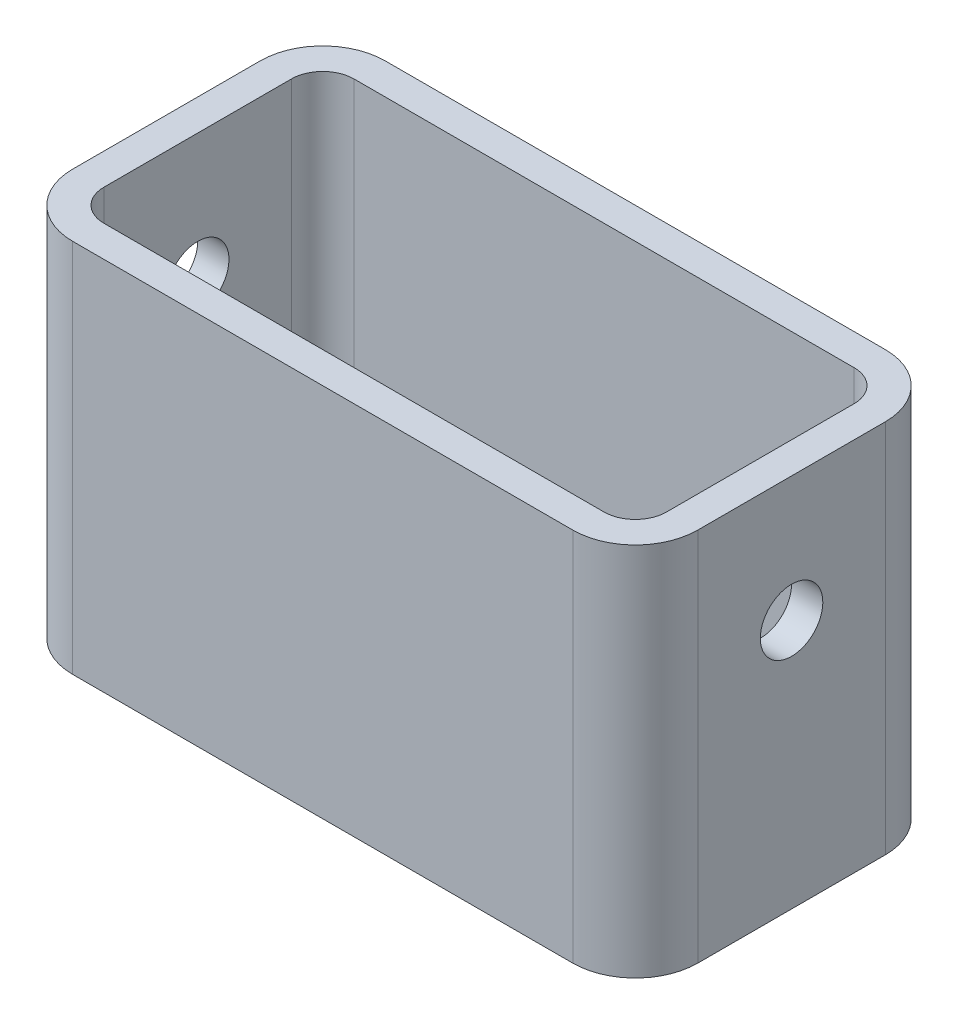
SolidWorks part; units mm, degrees
ref_plane "Front Plane" through (0, 0, 0) normal (0, 0, 1) x (1, 0, 0)
ref_plane "Top Plane" through (0, 0, 0) normal (0, 1, 0) x (1, 0, 0)
ref_plane "Right Plane" through (0, 0, 0) normal (1, 0, 0) x (0, 0, -1)
sketch "Sketch1" plane through (0, 0, 0) normal (0, 0, 1) x (1, 0, 0)
  line L1 (-46.5347, 26.9802) -> (53.4653, 26.9802)
  line L2 (-46.5347, 26.9802) -> (-46.5347, -33.0198)
  line L3 (-46.5347, -33.0198) -> (53.4653, -33.0198)
  line L4 (53.4653, 26.9802) -> (53.4653, -33.0198)
  dimension "D1" = 100
  dimension "D2" = 60
extrude "Boss-Extrude1" add sketch "Sketch1" along normal blind 50
fillet "Fillet1" radius 10 1 edges at (53.4653, -3.0198, 50)
fillet "Fillet2" radius 10 3 edges at (-46.5347, -3.0198, 50) (-46.5347, -3.0198, 0) (53.4653, -3.0198, 0)
shell "Shell1" thickness 5
sketch "Sketch2" plane through (53.4653, 0, 0) normal (1, 0, 0) x (0, 0, -1)
  line L0 (-50, -33.0198) -> (-50, 26.9802) construction
  line L1 (-40, -33.0198) -> (-10, -33.0198) construction
  circle A0 centre (-25, 6.9802) radius 5
  dimension "D1" = 10
  dimension "D2" = 25
  dimension "D3" = 40
extrude "Cut-Extrude1" cut sketch "Sketch2" against normal through all
